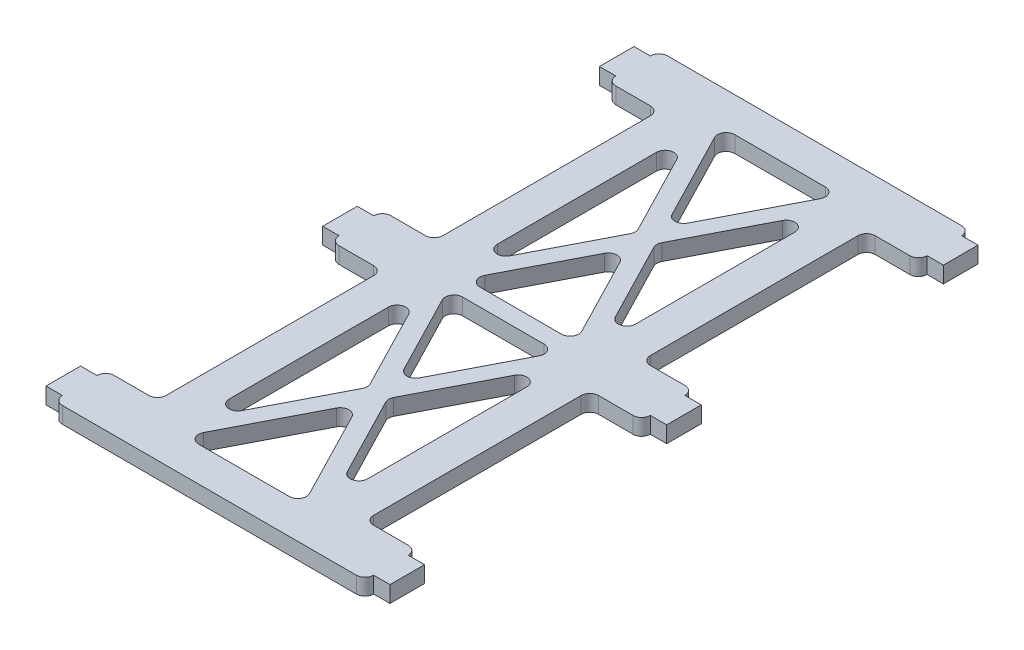
SolidWorks part; units mm, degrees
ref_plane "Front Plane" through (0, 0, 0) normal (0, 0, 1) x (1, 0, 0)
ref_plane "Top Plane" through (0, 0, 0) normal (0, 1, 0) x (1, 0, 0)
ref_plane "Right Plane" through (0, 0, 0) normal (1, 0, 0) x (0, 0, -1)
sketch "Sketch1" plane through (0, 34.29, 0) normal (0, 1, 0) x (1, 0, 0)
  line L0 (22.4028, 190.5) -> (25.4, 190.5) construction
  line L1 (0, -190.5) -> (0, 187.198) construction
  line L2 (38.1028, 187.198) -> (35.1028, 187.198) construction
  line L3 (35.1028, -190.5) -> (38.1, -190.5) construction
  line L5 (-19.05, 65.0875) -> (19.05, 65.0875)
  line L6 (-19.05, 65.0875) -> (-19.05, 176.2125)
  line L7 (-19.05, 176.2125) -> (19.05, 176.2125)
  line L8 (19.05, 65.0875) -> (19.05, 176.2125)
  line L9 (-19.05, 65.0875) -> (19.05, 176.2125) construction
  line L10 (-19.05, 176.2125) -> (19.05, 65.0875) construction
  point P0 (0, 120.65)
  dimension "D1" = 111.125
  dimension "D2" = 38.1
  dimension "D3" = 14.2875
extrude "Boss-Extrude1" add sketch "Sketch1" along normal mid plane 3 contours L7 L8 L5 L6
sketch "Sketch2" plane through (0, 35.79, 0) normal (0, 1, 0) x (1, 0, 0)
  line L0 (0, 176.2125) -> (0, 65.0186) construction
  line L1 (-19.05, 176.2125) -> (19.05, 176.2125) construction
  line L2 (19.05, 120.65) -> (-19.05, 120.65) construction
  line L3 (19.05, 65.0875) -> (19.05, 176.2125) construction
  line L4 (-19.05, 65.0875) -> (-19.05, 176.2125) construction
  line L5 (-28.575, 176.2125) -> (-19.05, 166.6875) construction
  line L6 (28.575, 166.6875) -> (19.05, 166.6875)
  line L7 (28.575, 166.6875) -> (28.575, 176.2125)
  line L8 (28.575, 176.2125) -> (19.05, 176.2125)
  line L9 (19.05, 166.6875) -> (19.05, 176.2125)
  line L10 (28.575, 166.6875) -> (19.05, 176.2125) construction
  line L11 (28.575, 176.2125) -> (19.05, 166.6875) construction
  line L12 (-28.575, 166.6875) -> (-19.05, 176.2125) construction
  line L13 (-19.05, 166.6875) -> (-19.05, 176.2125)
  line L14 (-28.575, 176.2125) -> (-19.05, 176.2125)
  line L15 (-28.575, 166.6875) -> (-28.575, 176.2125)
  line L16 (-28.575, 166.6875) -> (-19.05, 166.6875)
  line L17 (28.575, 115.8875) -> (19.05, 115.8875)
  line L18 (28.575, 115.8875) -> (28.575, 125.4125)
  line L19 (28.575, 125.4125) -> (19.05, 125.4125)
  line L20 (19.05, 115.8875) -> (19.05, 125.4125)
  line L21 (28.575, 115.8875) -> (19.05, 125.4125) construction
  line L22 (28.575, 125.4125) -> (19.05, 115.8875) construction
  line L23 (-19.05, 115.8875) -> (-19.05, 125.4125)
  line L24 (-28.575, 125.4125) -> (-19.05, 125.4125)
  line L25 (-28.575, 115.8875) -> (-28.575, 125.4125)
  line L26 (-28.575, 115.8875) -> (-19.05, 115.8875)
  line L27 (-28.575, 125.4125) -> (-19.05, 115.8875) construction
  line L28 (-28.575, 115.8875) -> (-19.05, 125.4125) construction
  line L29 (28.575, 65.0875) -> (19.05, 65.0875)
  line L30 (28.575, 65.0875) -> (28.575, 74.6125)
  line L31 (28.575, 74.6125) -> (19.05, 74.6125)
  line L32 (19.05, 65.0875) -> (19.05, 74.6125)
  line L33 (28.575, 65.0875) -> (19.05, 74.6125) construction
  line L34 (28.575, 74.6125) -> (19.05, 65.0875) construction
  line L35 (-19.05, 65.0875) -> (-19.05, 74.6125)
  line L36 (-28.575, 74.6125) -> (-19.05, 74.6125)
  line L37 (-28.575, 65.0875) -> (-28.575, 74.6125)
  line L38 (-28.575, 65.0875) -> (-19.05, 65.0875)
  line L39 (-28.575, 74.6125) -> (-19.05, 65.0875) construction
  line L40 (-28.575, 65.0875) -> (-19.05, 74.6125) construction
  point P11 (23.8125, 171.45)
  point P21 (-23.8125, 171.45)
  point P24 (23.8125, 120.65)
  point P33 (-23.8125, 120.65)
  point P34 (23.8125, 69.85)
  point P43 (-23.8125, 69.85)
  dimension "D1" = 9.525
  dimension "D2" = 9.525
  dimension "D3" = 3
extrude "Boss-Extrude2" add sketch "Sketch2" against normal up to surface (3 mm away) up to face at (0, 32.79, -120.65)
sketch "Sketch4" plane through (0, 35.79, 0) normal (0, 1, 0) x (1, 0, 0)
  line L0 (19.05, 125.4125) -> (19.05, 166.6875) construction
  line L1 (-12.7, 169.8625) -> (12.7, 169.8625)
  line L2 (-12.7, 169.8625) -> (-12.7, 71.4375)
  line L3 (-12.7, 71.4375) -> (12.7, 71.4375)
  line L4 (12.7, 169.8625) -> (12.7, 71.4375)
  line L5 (-12.7, 169.8625) -> (12.7, 71.4375) construction
  line L6 (-12.7, 71.4375) -> (12.7, 169.8625) construction
  line L7 (-19.05, 125.4125) -> (-19.05, 166.6875) construction
  line L8 (-28.575, 176.2125) -> (28.575, 176.2125) construction
  line L9 (-28.575, 65.0875) -> (28.575, 65.0875) construction
  line L10 (-12.7, 120.65) -> (12.7, 120.65) construction
  line L11 (12.7, 120.65) -> (-12.7, 169.8625) construction
  line L12 (12.7, 120.65) -> (-12.7, 71.4375) construction
  line L13 (-12.7, 120.65) -> (12.7, 169.8625) construction
  line L14 (12.7, 71.4375) -> (-12.7, 120.65) construction
  line L15 (-12.7, 119.0625) -> (12.7, 119.0625)
  line L16 (-12.7, 122.2375) -> (12.7, 122.2375)
  line L17 (14.1107, 72.1656) -> (-10.9135, 120.65)
  line L18 (-10.9135, 120.65) -> (14.1107, 169.1344)
  line L19 (14.4865, 120.65) -> (-11.2893, 70.7094)
  line L20 (14.4865, 120.65) -> (-11.2893, 170.5906)
  line L21 (11.2893, 70.7094) -> (-14.4865, 120.65)
  line L22 (-14.4865, 120.65) -> (11.2893, 170.5906)
  line L23 (10.9135, 120.65) -> (-14.1107, 72.1656)
  line L24 (10.9135, 120.65) -> (-14.1107, 169.1344)
  point P0 (0, 120.65)
  dimension "D1" = 6.35
  dimension "D2" = 6.35
  dimension "D3" = 6.35
  dimension "D4" = 6.35
  dimension "D5" = 1.5875
  dimension "D6" = 1.5875
  dimension "D7" = 1.5875
  dimension "D8" = 1.5875
extrude "Cut-Extrude1" cut sketch "Sketch4" against normal blind 3 contours L15 L19 L17 L4 | L3 L21 L19 | L23 L21 L15 L2 | L23 L15 L17 | L16 L24 L18 | L20 L16 L4 L18 | L20 L22 L1 | L22 L24 L2 L16
fillet "Fillet1" radius 1.5875 44 edges at (-10.0942, 34.29, -119.0625) (10.0942, 34.29, -119.0625) (0, 34.29, -99.505) (-12.7, 34.29, -117.1887) (-1.7865, 34.29, -96.0438) (-12.7, 34.29, -74.8988) (12.7, 34.29, -166.4012) (12.7, 34.29, -124.1113) (1.7865, 34.29, -145.2563) (10.9135, 34.29, -169.8625) (0, 34.29, -148.7175) (-10.9135, 34.29, -169.8625) (1.7865, 34.29, -96.0438) (12.7, 34.29, -117.1887) (12.7, 34.29, -74.8988) (28.575, 34.29, -65.0875) (28.575, 34.29, -74.6125) (19.05, 34.29, -74.6125) (19.05, 34.29, -115.8875) (28.575, 34.29, -115.8875) (28.575, 34.29, -125.4125) (19.05, 34.29, -125.4125) (19.05, 34.29, -166.6875) (28.575, 34.29, -166.6875) (28.575, 34.29, -176.2125) (-28.575, 34.29, -166.6875) (-19.05, 34.29, -166.6875) (-19.05, 34.29, -125.4125) (-28.575, 34.29, -125.4125) (-28.575, 34.29, -115.8875) (-19.05, 34.29, -115.8875) (-19.05, 34.29, -74.6125) (-28.575, 34.29, -74.6125) (-28.575, 34.29, -65.0875) (-12.7, 34.29, -124.1113) (-12.7, 34.29, -166.4012) (-1.7865, 34.29, -145.2563) (-10.9135, 34.29, -71.4375) (0, 34.29, -92.5825) (10.9135, 34.29, -71.4375) (-10.0942, 34.29, -122.2375) (0, 34.29, -141.795) (10.0942, 34.29, -122.2375) (-28.575, 34.29, -176.2125)
sketch "Sketch5" plane through (0, 35.79, 0) normal (0, 1, 0) x (1, 0, 0)
  line L0 (28.575, 168.275) -> (28.575, 174.625) construction
  line L1 (31.575, 168.275) -> (28.575, 168.275)
  line L2 (31.575, 168.275) -> (31.575, 174.625)
  line L3 (31.575, 174.625) -> (28.575, 174.625)
  line L4 (28.575, 168.275) -> (28.575, 174.625)
  line L5 (31.575, 168.275) -> (28.575, 174.625) construction
  line L6 (31.575, 174.625) -> (28.575, 168.275) construction
  line L7 (28.575, 168.275) -> (28.575, 174.625) construction
  line L8 (28.575, 171.45) -> (30.075, 171.45) construction
  line L9 (0, 196.0278) -> (0, 0) construction
  line L10 (-28.575, 171.45) -> (-30.075, 171.45) construction
  line L11 (-31.575, 174.625) -> (-28.575, 168.275) construction
  line L12 (-31.575, 168.275) -> (-28.575, 174.625) construction
  line L13 (-28.575, 168.275) -> (-28.575, 174.625)
  line L14 (-31.575, 174.625) -> (-28.575, 174.625)
  line L15 (-31.575, 168.275) -> (-31.575, 174.625)
  line L16 (-31.575, 168.275) -> (-28.575, 168.275)
  line L17 (31.575, 117.475) -> (28.575, 117.475)
  line L18 (31.575, 117.475) -> (31.575, 123.825)
  line L19 (31.575, 123.825) -> (28.575, 123.825)
  line L20 (28.575, 117.475) -> (28.575, 123.825)
  line L21 (31.575, 117.475) -> (28.575, 123.825) construction
  line L22 (31.575, 123.825) -> (28.575, 117.475) construction
  line L23 (28.575, 120.65) -> (30.075, 120.65) construction
  line L24 (-28.575, 117.475) -> (-28.575, 123.825)
  line L25 (-31.575, 123.825) -> (-28.575, 123.825)
  line L26 (-31.575, 117.475) -> (-31.575, 123.825)
  line L27 (-31.575, 117.475) -> (-28.575, 117.475)
  line L28 (-28.575, 120.65) -> (-30.075, 120.65) construction
  line L29 (-31.575, 123.825) -> (-28.575, 117.475) construction
  line L30 (-31.575, 117.475) -> (-28.575, 123.825) construction
  line L31 (31.575, 66.675) -> (28.575, 66.675)
  line L32 (31.575, 66.675) -> (31.575, 73.025)
  line L33 (31.575, 73.025) -> (28.575, 73.025)
  line L34 (28.575, 66.675) -> (28.575, 73.025)
  line L35 (31.575, 66.675) -> (28.575, 73.025) construction
  line L36 (31.575, 73.025) -> (28.575, 66.675) construction
  line L37 (28.575, 69.85) -> (30.075, 69.85) construction
  line L38 (-28.575, 66.675) -> (-28.575, 73.025)
  line L39 (-31.575, 73.025) -> (-28.575, 73.025)
  line L40 (-31.575, 66.675) -> (-31.575, 73.025)
  line L41 (-31.575, 66.675) -> (-28.575, 66.675)
  line L42 (-28.575, 69.85) -> (-30.075, 69.85) construction
  line L43 (-31.575, 73.025) -> (-28.575, 66.675) construction
  line L44 (-31.575, 66.675) -> (-28.575, 73.025) construction
  line L45 (-30.075, 171.45) -> (-30.075, 120.65) construction
  point P0 (30.075, 171.45)
  point P7 (30.075, 120.65)
  point P21 (-30.075, 171.45)
  point P35 (-30.075, 120.65)
  point P36 (30.075, 69.85)
  point P49 (-30.075, 69.85)
  dimension "D1" = 3
  dimension "D2" = 6.35
  dimension "D4" = 50.8
  dimension "D3" = 3
extrude "Boss-Extrude3" add sketch "Sketch5" against normal up to surface (3 mm away)
